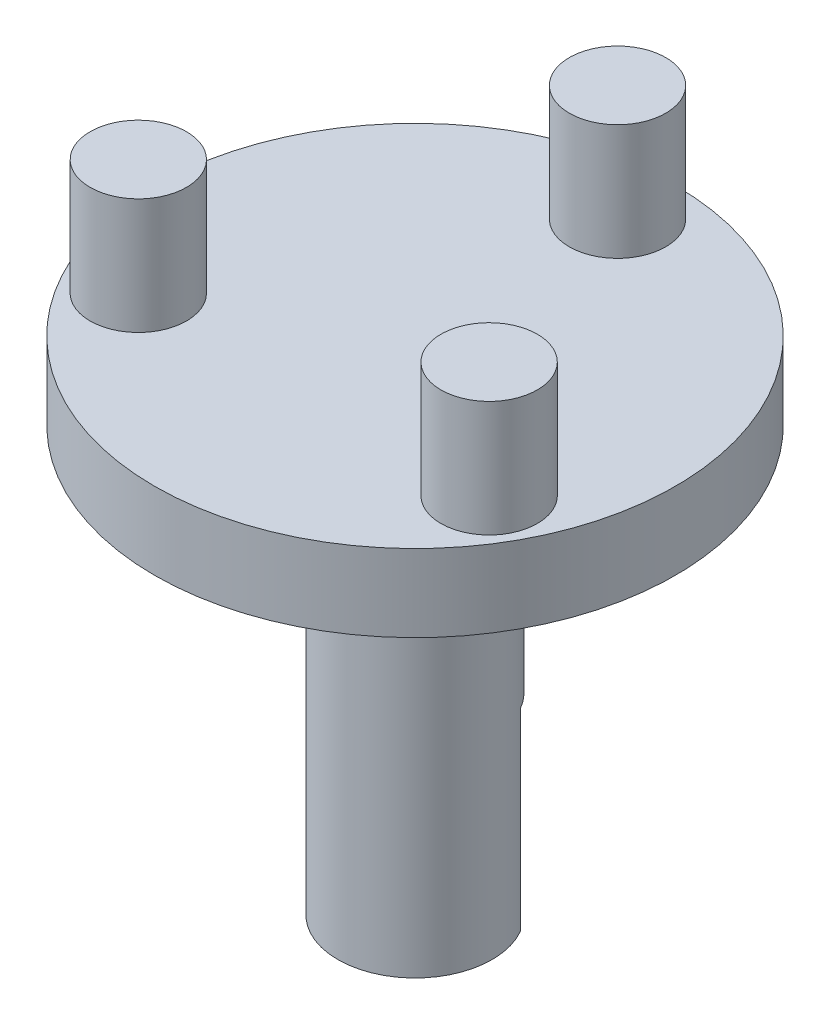
SolidWorks part; units mm, degrees
ref_plane "前视基准面" through (0, 0, 0) normal (0, 0, 1) x (1, 0, 0)
ref_plane "上视基准面" through (0, 0, 0) normal (0, 1, 0) x (1, 0, 0)
ref_plane "右视基准面" through (0, 0, 0) normal (1, 0, 0) x (0, 0, -1)
sketch "草图1" plane through (0, 0, 0) normal (0, 1, 0) x (1, 0, 0)
  circle A0 centre (0, 0) radius 13.5
  dimension "D1" = 27
extrude "凸台-拉伸1" add sketch "草图1" along normal blind 4
sketch "草图2" plane through (0, 4, 0) normal (0, 1, 0) x (1, 0, 0)
  line L0 (0, 0) -> (0, 10.5) construction
  circle A0 centre (0, 0) radius 10.5 construction
  circle A1 centre (0, 10.5) radius 2.5
  circle A2 centre (9.0933, -5.25) radius 2.5
  circle A3 centre (-9.0933, -5.25) radius 2.5
  point P12 (0, 0)
  dimension "D1" = 21
  dimension "D2" = 5
  dimension "D3" = 3
extrude "凸台-拉伸2" add sketch "草图2" along normal blind 6
sketch "草图3" plane through (0, 0, 0) normal (0, -1, 0) x (1, 0, 0)
  circle A0 centre (0, 0) radius 4
  dimension "D1" = 8
extrude "凸台-拉伸3" add sketch "草图3" along normal blind 7
sketch "草图4" plane through (0, 0, 0) normal (0, -1, 0) x (1, 0, 0)
  circle A0 centre (0, 0) radius 5.5
  dimension "D1" = 11
extrude "凸台-拉伸4" add sketch "草图4" along normal blind 1
sketch "草图5" plane through (0, -7, 0) normal (0, -1, 0) x (1, 0, 0)
  circle A1 centre (0, 0) radius 4
  circle A2 centre (0, 0) radius 4
  dimension "D1" = 0
extrude "凸台-拉伸5" add sketch "草图5" along normal blind 15
sketch "草图6" plane through (0, -22, 0) normal (0, -1, 0) x (1, 0, 0)
  line L0 (3.4641, -2) -> (-3.4641, -2)
  line L1 (-3.4641, -2) -> (0, 0) construction
  line L2 (0, 0) -> (3.4641, -2) construction
  circle A0 centre (0, 0) radius 4 construction
  circle A2 centre (0, 0) radius 4
  arc A3 (-3.4641, -2) -> (3.4641, -2) centre (0, 0) ccw
  dimension "D1" = 120
  dimension "D2" = 0
extrude "切除-拉伸1" cut sketch "草图6" against normal blind 10
sketch "草图7" plane through (0, 0, -2) normal (0, 0, -1) x (-1, 0, 0)
  line L0 (0, -12) -> (0, -22) construction
  line L1 (-3.4641, -12) -> (3.4641, -12) construction
  line L2 (-3.4641, -22) -> (3.4641, -22) construction
  line L3 (-13.5, 0) -> (13.5, 0) construction
  circle A0 centre (0, -15.5) radius 1.5
  point P8 (0, -17.6873)
  dimension "D1" = 3
  dimension "D2" = 15.5
extrude "切除-拉伸2" cut sketch "草图7" against normal blind 1
